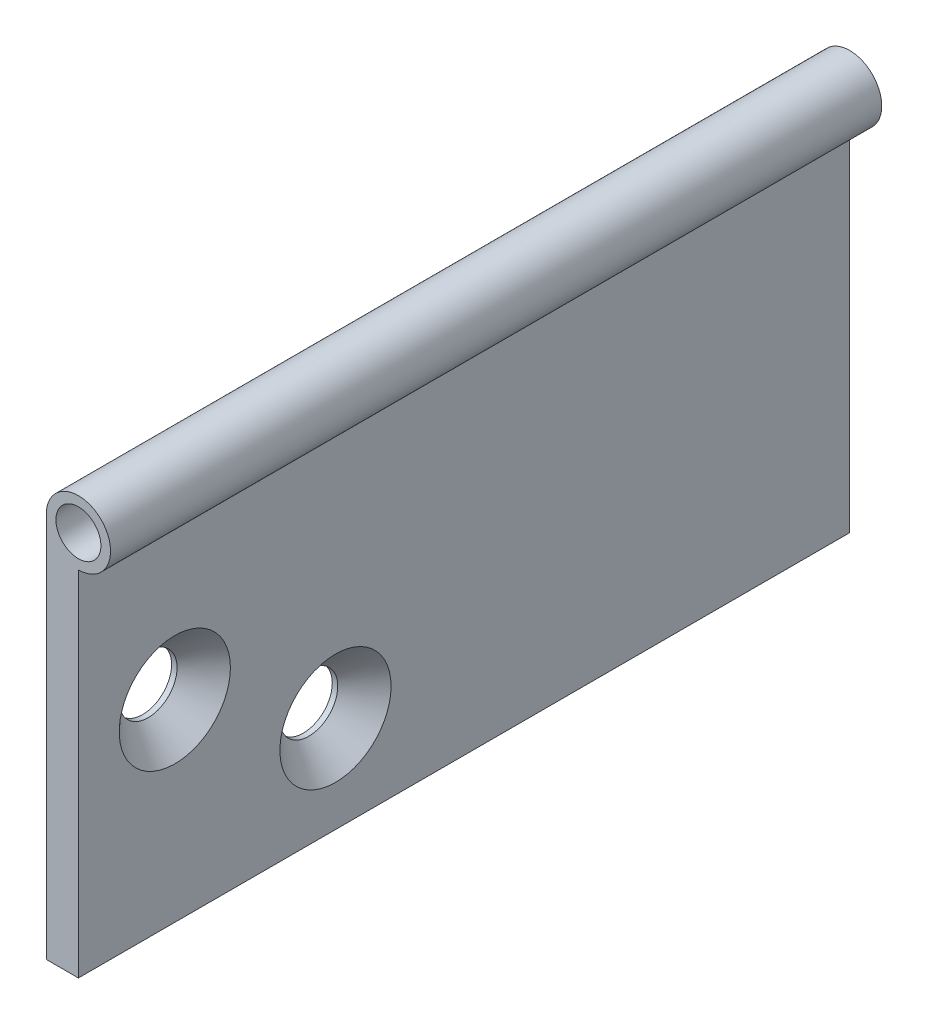
SolidWorks part; units mm, degrees
ref_plane "Front" through (0, 0, 0) normal (0, 0, 1) x (1, 0, 0)
ref_plane "Top" through (0, 0, 0) normal (0, 1, 0) x (1, 0, 0)
ref_plane "Right" through (0, 0, 0) normal (1, 0, 0) x (0, 0, -1)
sketch "Эскиз1" plane through (0, 0, 0) normal (0, 0, 1) x (1, 0, 0)
  line L0 (0, 0) -> (0, 60)
  dimension "D1" = 60
extrude "Вытянуть-Тонкостенный1" add sketch "Эскиз1" along normal mid plane 120 thin
sketch "Эскиз2" plane through (0, 0, 60) normal (0, 0, 1) x (1, 0, 0)
  circle A0 centre (5, 60) radius 5
sweep "По траектории1" add profiles "Эскиз2" path edge at (5, 60, 0)
sketch "Эскиз3" plane through (0, 0, 60) normal (0, 0, 1) x (1, 0, 0)
  circle A0 centre (5, 60) radius 3.5
  arc A1 (5, 55) -> (0, 60) centre (5, 60) ccw construction
  dimension "D1" = 7
extrude "Вырез-Вытянуть1" cut sketch "Эскиз3" against normal through all
hole_wizard "Зенковка для  винта с плоской головкой M84" positions "Эскиз12" profile "Эскиз11" countersink size "M8" standard "Ansi Metric" end condition through all
sketch "Эскиз12" plane through (5, 0, 0) normal (1, 0, 0) x (0, 0, -1)
  line L0 (-60, 0) -> (-60, 55) construction
  line L1 (-60, 0) -> (60, 0) construction
  line L2 (-60, 0) -> (-60, 60) construction
  point P0 (-45, 30)
  point P2 (-20, 15)
  dimension "D1" = 15
  dimension "D2" = 30
  dimension "D3" = 40
  dimension "D4" = 15
sketch "Эскиз11" plane through (5, 30, 45) normal (0, 1, 0) x (0, 0, -1)
  line L0 (0, 0) -> (0, 5)
  line L1 (0, 5) -> (4.5, 5)
  line L2 (4.5, 5) -> (4.5, 4.15)
  line L3 (4.5, 4.15) -> (8.65, 0)
  line L5 (8.65, 0) -> (0, 0)
  line L6 (-4.5, 4.15) -> (-8.65, 0) construction
  line L11 (0, -6.35) -> (0, 107.95) construction
  dimension "Диаметр сквозного отверстия" = 9
  dimension "Глубина сквозного отверстия" = 5
  dimension "Диаметр передней зенковки" = 17.3
  dimension "Угол передней зенковки" = 90
